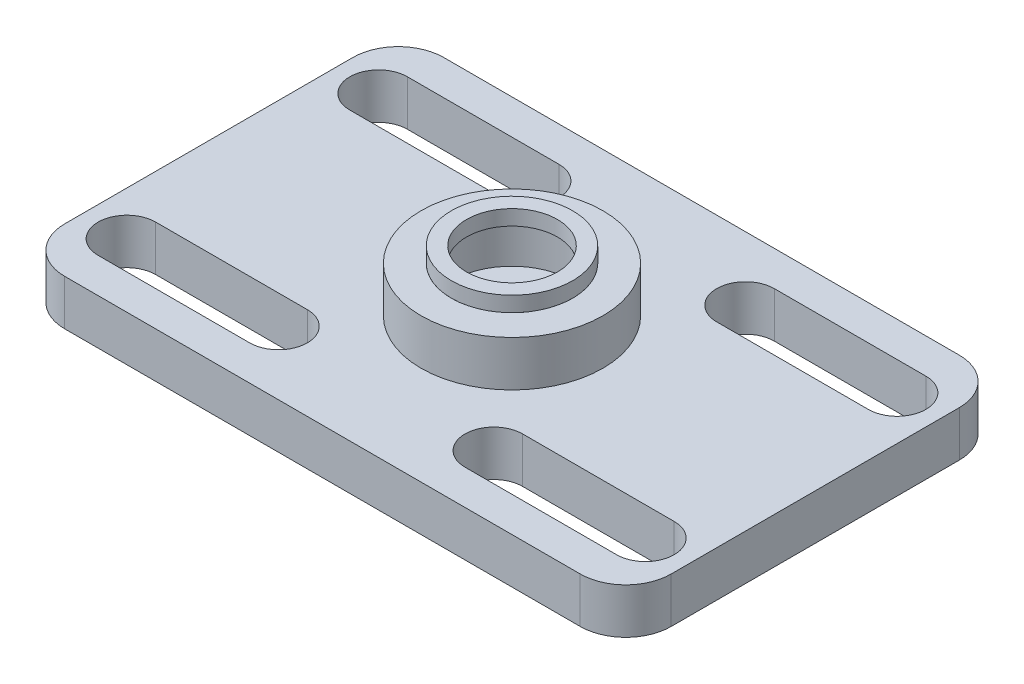
SolidWorks part; units mm, degrees
material "Cast Alloy Steel"
ref_plane "Front Plane" through (0, 0, 0) normal (0, 0, 1) x (1, 0, 0)
ref_plane "Top Plane" through (0, 0, 0) normal (0, 1, 0) x (1, 0, 0)
ref_plane "Right Plane" through (0, 0, 0) normal (1, 0, 0) x (0, 0, -1)
sketch "Sketch2" plane through (0, 0, 0) normal (0, 1, 0) x (1, 0, 0)
  circle A0 centre (0, 0) radius 15
  circle A1 centre (0, 0) radius 20
  dimension "D1" = 30
  dimension "D2" = 40
extrude "Boss-Extrude1" add sketch "Sketch2" against normal blind 5
sketch "Sketch3" plane through (0, -5, 0) normal (0, -1, 0) x (1, 0, 0)
  circle A0 centre (0, 0) radius 30
  circle A1 centre (0, 0) radius 20
  dimension "D1" = 60
  dimension "D2" = 40
extrude "Boss-Extrude2" add sketch "Sketch3" along normal blind 15 separate body
sketch "Sketch4" plane through (0, -20, 0) normal (0, -1, 0) x (1, 0, 0)
  line L1 (-100, 62.5) -> (100, 62.5)
  line L2 (-100, 62.5) -> (-100, -62.5)
  line L3 (-100, -62.5) -> (100, -62.5)
  line L4 (100, 62.5) -> (100, -62.5)
  line L5 (-100, 62.5) -> (100, -62.5) construction
  line L6 (-100, -62.5) -> (100, 62.5) construction
  point P0 (0, 0)
  dimension "D1" = 200
  dimension "D2" = 125
extrude "Boss-Extrude3" add sketch "Sketch4" along normal blind 15
fillet "Fillet1" radius 15 4 edges at (-100, -27.5, -62.5) (-100, -27.5, 62.5) (100, -27.5, -62.5) (100, -27.5, 62.5)
sketch "Sketch5" plane through (0, -20, 0) normal (0, 1, 0) x (1, 0, 0)
  line L0 (-85.5, -41.5) -> (-35.5, -41.5) construction
  line L1 (-85.5, -32) -> (-35.5, -32)
  line L2 (-85.5, -51) -> (-35.5, -51)
  line L3 (-100, -47.5) -> (-100, 47.5) construction
  line L4 (85, -62.5) -> (-85, -62.5) construction
  arc A0 (-85.5, -32) -> (-85.5, -51) centre (-85.5, -41.5) ccw
  arc A1 (-35.5, -51) -> (-35.5, -32) centre (-35.5, -41.5) ccw
  point P2 (-60.5, -41.5)
  point P7 (0, 0)
  point P8 (0, 0)
  dimension "D2" = 9.5
  dimension "D1" = 50
  dimension "D3" = 14.5
  dimension "D4" = 11.5
extrude "Cut-Extrude1" cut sketch "Sketch5" against normal through all contours L2 A1 L1 A0
mirror "Mirror1" about plane through (0, 0, 0) normal (0, 0, 1) of "Cut-Extrude1"
mirror "Mirror2" about plane through (0, 0, 0) normal (1, 0, 0) of "Mirror1", "Cut-Extrude1"
